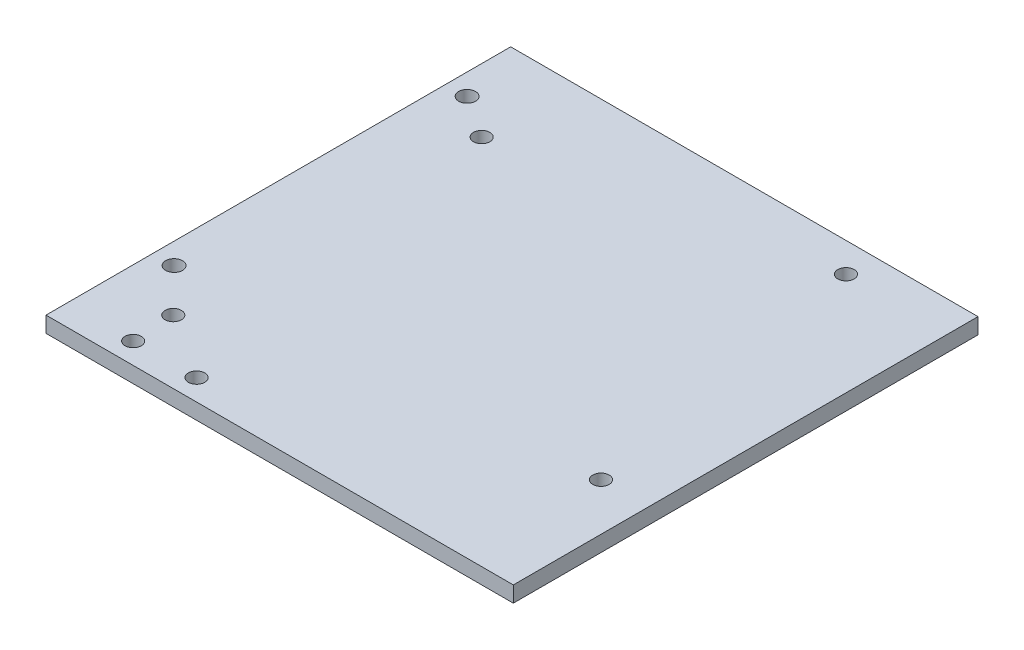
SolidWorks part; units mm, degrees
ref_plane "Front Plane" through (0, 0, 0) normal (0, 0, 1) x (1, 0, 0)
ref_plane "Top Plane" through (0, 0, 0) normal (0, 1, 0) x (1, 0, 0)
ref_plane "Right Plane" through (0, 0, 0) normal (1, 0, 0) x (0, 0, -1)
sketch "Sketch1" plane through (0, 0, 0) normal (0, 1, 0) x (1, 0, 0)
  line L0 (-36.2, -37.5) -> (-36.2, -40) construction
  line L1 (-40.25, -40) -> (40.25, -40) construction
  line L2 (-40.25, -40) -> (-40.25, 40) construction
  line L3 (-40.25, 40) -> (40.25, 40)
  line L4 (40.25, -40) -> (40.25, 40)
  line L5 (-40.25, -40) -> (40.25, 40) construction
  line L6 (-40.25, 40) -> (40.25, -40) construction
  line L7 (-37.75, -35.95) -> (-40.25, -35.95) construction
  line L8 (-36.2, 24) -> (-36.2, 40) construction
  line L9 (20.8, 36) -> (20.8, 40) construction
  line L10 (19.25, 34.45) -> (-40.25, 34.45) construction
  line L11 (29.75, -22.45) -> (-40.25, -22.45) construction
  line L12 (31.3, -24) -> (31.3, -40) construction
  line L13 (-40.25, 40) -> (-48.25, 40)
  line L14 (-48.25, 40) -> (-48.25, -40)
  line L15 (-48.25, -40) -> (-40.25, -40) construction
  line L16 (-44.25, 40) -> (-44.25, 27.75) construction
  line L17 (-44.25, 27.75) -> (-44.25, -27.75) construction
  line L18 (-44.25, -27.75) -> (-44.25, -40) construction
  line L19 (-48.25, -40) -> (-48.25, -48)
  line L20 (-48.25, -48) -> (40.25, -48)
  line L21 (40.25, -48) -> (40.25, -40)
  line L22 (-48.25, -44) -> (40.25, -44) construction
  circle A0 centre (-36.2, -35.95) radius 1.55
  circle A1 centre (-36.2, 22.45) radius 1.55
  circle A2 centre (20.8, 34.45) radius 1.55
  circle A3 centre (31.3, -22.45) radius 1.55
  circle A4 centre (-44.25, 27.75) radius 1.6
  circle A5 centre (-44.25, -27.75) radius 1.6
  circle A6 centre (-29.74, -44) radius 1.55 construction
  circle A7 centre (-35.74, -44) radius 1.55
  circle A8 centre (-23.74, -44) radius 1.55
  point P0 (0, 0)
  dimension "D3" = 3.1
  dimension "D5" = 16
  dimension "D6" = 4
  dimension "D8" = 70
  dimension "D12" = 3.2
  dimension "D14" = 18.51
  dimension "D15" = 3.1
  dimension "D16" = 6
  dimension "D1" = 80
  dimension "D2" = 80.5
  dimension "D4" = 2.5
  dimension "D7" = 59.5
  dimension "D9" = 16
  dimension "D10" = 8
  dimension "D11" = 55.5
  dimension "D13" = 8
  dimension "D17" = 6
extrude "Boss-Extrude1" add sketch "Sketch1" along normal blind 3
